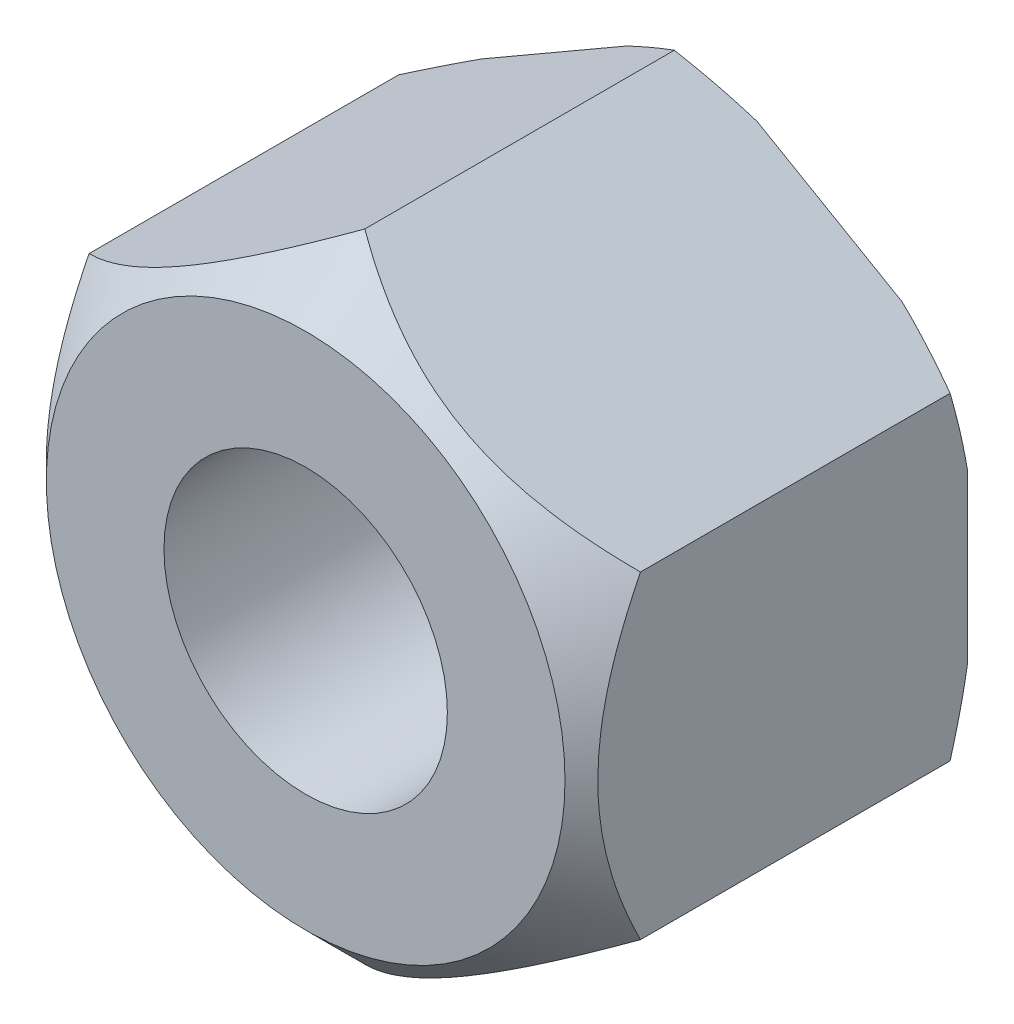
SolidWorks part; units mm, degrees
ref_plane "基准面1" through (0, 0, 0) normal (0, 0, 1) x (1, 0, 0)
ref_plane "基准面2" through (0, 0, 0) normal (0, 1, 0) x (1, 0, 0)
ref_plane "基准面3" through (0, 0, 0) normal (1, 0, 0) x (0, 0, -1)
sketch "尺寸草图" plane through (0, 0, 0) normal (0, 0, 1) x (1, 0, 0)
  line L0 (0, 0) -> (15.63, 0)
  line L1 (0, 0) -> (6.75, 0)
  line L2 (6.75, 0) -> (15.63, 0)
  line L3 (-5.7143, 0) -> (0, 0)
  point P3 (6, 0)
  point P4 (1, 0)
  point P5 (11.05, 0)
  point P7 (4.32, 0)
  point P8 (10, 0)
  point P15 (13.45, 0)
  dimension "D1" = 5.7143
  dimension "D" = 6
  dimension "P" = 1
  dimension "e(min)" = 11.05
  dimension "mw(min)" = 4.32
  dimension "s(max)" = 10
  dimension "da(max)" = 6.75
  dimension "dw(min)" = 8.88
  dimension "h(max)" = 6.7
sketch "草图1" plane through (0, 0, 0) normal (0, 0, 1) x (1, 0, 0)
  line L0 (-4.7848, 0) -> (4.7848, 0) construction
  line L1 (0, 5.525) -> (0, -5.525) construction
  line L3 (0, 5.525) -> (-4.7848, 2.7625)
  line L4 (-4.7848, 2.7625) -> (-4.7848, -2.7625)
  line L5 (-4.7848, -2.7625) -> (0, -5.525)
  line L6 (0, -5.525) -> (4.7848, -2.7625)
  line L7 (4.7848, -2.7625) -> (4.7848, 2.7625)
  line L8 (4.7848, 2.7625) -> (0, 5.525)
  circle A0 centre (0, 0) radius 4.7848 construction
  circle A1 centre (0, 0) radius 2.4588
  dimension "D" = 4.9175
  dimension "e" = 11.05
extrude "基体-拉伸" add sketch "草图1" along normal blind 6.7
cosmetic thread "装饰螺纹线1" parameters "D2"=6
sketch "草图2" plane through (0, 0, 0) normal (0, 0, -1) x (-1, 0, 0)
  circle A0 centre (0, 0) radius 5
  circle A1 centre (0, 0) radius 2.4588 construction
  dimension "s" = 10
extrude "切除-拉伸1" cut sketch "草图2" against normal through all draft 60 flip side to cut
chamfer "倒角1" distance 0.1295 angle 45 1 edges at (2.4588, 0, 0)
sketch "草图9" plane through (0, 0, 6.7) normal (0, 0, 1) x (1, 0, 0)
  circle A0 centre (0, 0) radius 4.5
  dimension "s*0.9" = 9
extrude "切除-拉伸7" cut sketch "草图9" against normal through all draft 45 flip side to cut
